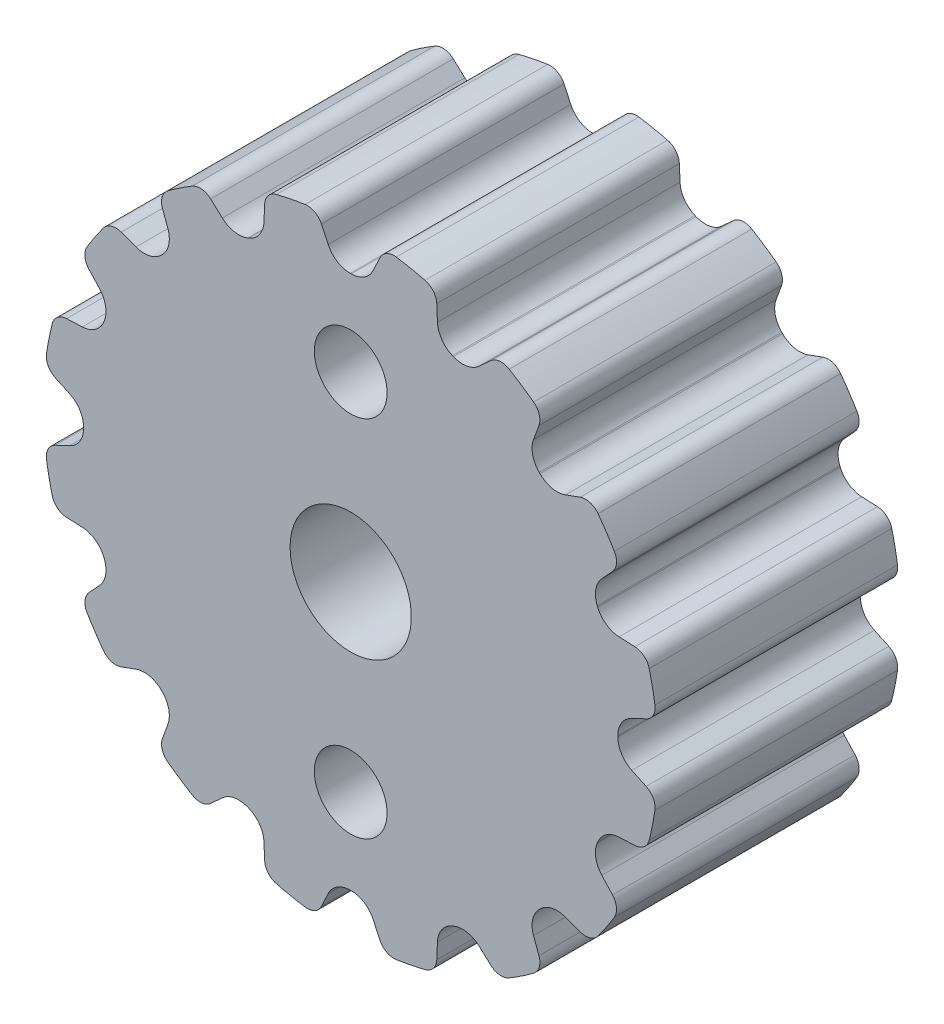
SolidWorks part; units mm, degrees
ref_plane "Спереди" through (0, 0, 0) normal (0, 0, 1) x (1, 0, 0)
ref_plane "Сверху" through (0, 0, 0) normal (0, 1, 0) x (1, 0, 0)
ref_plane "Справа" through (0, 0, 0) normal (1, 0, 0) x (0, 0, -1)
sketch "Эскиз1" plane through (0, 0, 0) normal (0, 0, 1) x (1, 0, 0)
  line L0 (-31.3394, -7.4998) -> (-31.3394, 5.1802) construction
  line L1 (-26.487, 4.215) -> (-31.3394, -7.4998) construction
  line L2 (-22.3733, 1.4663) -> (-31.3394, -7.4998) construction
  line L3 (-19.6246, -2.6474) -> (-31.3394, -7.4998) construction
  line L4 (-18.6594, -7.4998) -> (-31.3394, -7.4998) construction
  line L5 (-19.6246, -12.3523) -> (-31.3394, -7.4998) construction
  line L6 (-22.3733, -16.466) -> (-31.3394, -7.4998) construction
  line L7 (-26.487, -19.2146) -> (-31.3394, -7.4998) construction
  line L8 (-31.3394, -20.1798) -> (-31.3394, -7.4998) construction
  line L9 (-36.1919, -19.2146) -> (-31.3394, -7.4998) construction
  line L10 (-40.3056, -16.466) -> (-31.3394, -7.4998) construction
  line L11 (-43.0542, -12.3523) -> (-31.3394, -7.4998) construction
  line L12 (-44.0194, -7.4998) -> (-31.3394, -7.4998) construction
  line L13 (-43.0542, -2.6474) -> (-31.3394, -7.4998) construction
  line L14 (-40.3056, 1.4663) -> (-31.3394, -7.4998) construction
  line L15 (-36.1919, 4.215) -> (-31.3394, -7.4998) construction
  line L16 (-31.3624, 3.5104) -> (-31.3165, 3.5104)
  line L17 (-35.5741, 2.6635) -> (-35.5317, 2.6811)
  line L18 (-39.1411, 0.2694) -> (-39.1086, 0.3018)
  line L19 (-41.5203, -3.3076) -> (-41.5028, -3.2652)
  line L20 (-42.3497, -7.4769) -> (-42.3497, -7.5228)
  line L21 (-41.5203, -11.6921) -> (-41.5028, -11.7345)
  line L22 (-39.1411, -15.269) -> (-39.1086, -15.3015)
  line L23 (-35.5741, -17.6632) -> (-35.5317, -17.6807)
  line L24 (-31.3624, -18.5101) -> (-31.3165, -18.5101)
  line L25 (-27.1472, -17.6807) -> (-27.1048, -17.6632)
  line L26 (-23.5702, -15.3015) -> (-23.5378, -15.269)
  line L27 (-21.1585, -11.6921) -> (-21.1761, -11.7345)
  line L28 (-20.3292, -7.4769) -> (-20.3292, -7.5228)
  line L29 (-21.1761, -3.2652) -> (-21.1585, -3.3076)
  line L30 (-23.5702, 0.3018) -> (-23.5378, 0.2694)
  line L31 (-27.1472, 2.6811) -> (-27.1048, 2.6635)
  line L32 (-34.9153, 3.5613) -> (-34.8869, 4.2116)
  line L33 (-32.2687, 4.0878) -> (-32.5438, 4.6777)
  line L34 (-30.4102, 4.0878) -> (-30.1351, 4.6777)
  line L35 (-27.7636, 3.5613) -> (-27.7919, 4.2116)
  line L36 (-26.0465, 2.8501) -> (-25.5667, 3.2898)
  line L37 (-23.8028, 1.3509) -> (-23.5802, 1.9625)
  line L38 (-22.4887, 0.0368) -> (-21.8771, 0.2594)
  line L39 (-20.9895, -2.2069) -> (-20.5498, -1.7271)
  line L40 (-20.2783, -3.924) -> (-19.628, -3.9523)
  line L41 (-19.7518, -6.5706) -> (-19.1619, -6.2955)
  line L42 (-19.7518, -8.4291) -> (-19.1619, -8.7042)
  line L43 (-20.2783, -11.0757) -> (-19.628, -11.0473)
  line L44 (-20.9895, -12.7927) -> (-20.5498, -13.2726)
  line L45 (-22.4887, -15.0365) -> (-21.8771, -15.2591)
  line L46 (-23.8028, -16.3506) -> (-23.5802, -16.9622)
  line L47 (-26.0465, -17.8498) -> (-25.5667, -18.2895)
  line L48 (-27.7636, -18.561) -> (-27.7919, -19.2113)
  line L49 (-30.4102, -19.0875) -> (-30.1351, -19.6774)
  line L50 (-32.2687, -19.0875) -> (-32.5438, -19.6774)
  line L51 (-34.9153, -18.561) -> (-34.8869, -19.2113)
  line L52 (-36.6323, -17.8498) -> (-37.1122, -18.2895)
  line L53 (-38.8761, -16.3506) -> (-39.0987, -16.9622)
  line L54 (-40.1902, -15.0365) -> (-40.8018, -15.2591)
  line L55 (-41.6894, -12.7927) -> (-42.1291, -13.2726)
  line L56 (-42.4006, -11.0757) -> (-43.0509, -11.0473)
  line L57 (-42.9271, -8.4291) -> (-43.517, -8.7042)
  line L58 (-42.9271, -6.5706) -> (-43.517, -6.2955)
  line L59 (-42.4006, -3.924) -> (-43.0509, -3.9523)
  line L60 (-41.6894, -2.2069) -> (-42.1291, -1.7271)
  line L61 (-40.1902, 0.0368) -> (-40.8018, 0.2594)
  line L62 (-38.8761, 1.3509) -> (-39.0987, 1.9625)
  line L63 (-36.6323, 2.8501) -> (-37.1122, 3.2898)
  arc A0 (-28.2768, 4.8047) -> (-29.4602, 5.0401) centre (-31.3394, -7.4998) ccw
  arc A1 (-23.8011, 2.6961) -> (-24.8044, 3.3664) centre (-31.3394, -7.4998) ccw
  arc A2 (-20.4732, -0.9648) -> (-21.1435, 0.0385) centre (-31.3394, -7.4998) ccw
  arc A3 (-18.7995, -5.6206) -> (-19.0349, -4.4372) centre (-31.3394, -7.4998) ccw
  arc A4 (-19.0349, -10.5625) -> (-18.7995, -9.379) centre (-31.3394, -7.4998) ccw
  arc A5 (-21.1435, -15.0382) -> (-20.4732, -14.0348) centre (-31.3394, -7.4998) ccw
  arc A6 (-24.8044, -18.3661) -> (-23.8011, -17.6957) centre (-31.3394, -7.4998) ccw
  arc A7 (-29.4602, -20.0398) -> (-28.2768, -19.8044) centre (-31.3394, -7.4998) ccw
  arc A8 (-34.4021, -19.8044) -> (-33.2186, -20.0398) centre (-31.3394, -7.4998) ccw
  arc A9 (-38.8777, -17.6957) -> (-37.8744, -18.3661) centre (-31.3394, -7.4998) ccw
  arc A10 (-42.2057, -14.0348) -> (-41.5353, -15.0382) centre (-31.3394, -7.4998) ccw
  arc A11 (-43.8794, -9.379) -> (-43.644, -10.5625) centre (-31.3394, -7.4998) ccw
  arc A12 (-43.644, -4.4372) -> (-43.8794, -5.6206) centre (-31.3394, -7.4998) ccw
  arc A13 (-41.5353, 0.0385) -> (-42.2057, -0.9648) centre (-31.3394, -7.4998) ccw
  arc A14 (-37.8744, 3.3664) -> (-38.8777, 2.6961) centre (-31.3394, -7.4998) ccw
  arc A15 (-33.2187, 5.0401) -> (-34.4021, 4.8047) centre (-31.3394, -7.4998) ccw
  arc A16 (-37.1122, 3.2898) -> (-37.8744, 3.3664) centre (-37.5446, 2.818) ccw
  arc A17 (-34.8869, 4.2116) -> (-34.4021, 4.8047) centre (-34.2475, 4.1837) cw
  arc A18 (-32.5438, 4.6777) -> (-33.2187, 5.0401) centre (-33.1239, 4.4072) ccw
  arc A19 (-30.1351, 4.6777) -> (-29.4602, 5.0401) centre (-29.5551, 4.4072) cw
  arc A20 (-27.7919, 4.2116) -> (-28.2768, 4.8047) centre (-28.4313, 4.1837) ccw
  arc A21 (-25.5667, 3.2898) -> (-24.8044, 3.3664) centre (-25.1343, 2.818) cw
  arc A22 (-23.5802, 1.9625) -> (-23.8011, 2.6961) centre (-24.1816, 2.1814) ccw
  arc A23 (-21.8771, 0.2594) -> (-21.1435, 0.0385) centre (-21.6582, -0.342) cw
  arc A24 (-20.5498, -1.7271) -> (-20.4732, -0.9648) centre (-21.0216, -1.2947) ccw
  arc A25 (-19.1619, -6.2955) -> (-18.7995, -5.6206) centre (-19.4324, -5.7155) ccw
  arc A26 (-19.0349, -4.4372) -> (-19.628, -3.9523) centre (-19.6559, -4.5917) ccw
  arc A27 (-18.7995, -9.379) -> (-19.1619, -8.7042) centre (-19.4324, -9.2842) ccw
  arc A28 (-19.0349, -10.5625) -> (-19.628, -11.0473) centre (-19.6559, -10.4079) cw
  arc A29 (-20.5498, -13.2726) -> (-20.4732, -14.0348) centre (-21.0216, -13.705) cw
  arc A30 (-21.1435, -15.0382) -> (-21.8771, -15.2591) centre (-21.6582, -14.6577) cw
  arc A31 (-23.5802, -16.9622) -> (-23.8011, -17.6957) centre (-24.1816, -17.1811) cw
  arc A32 (-24.8044, -18.3661) -> (-25.5667, -18.2895) centre (-25.1343, -17.8177) cw
  arc A33 (-27.7919, -19.2113) -> (-28.2768, -19.8044) centre (-28.4313, -19.1834) cw
  arc A34 (-29.4602, -20.0398) -> (-30.1351, -19.6774) centre (-29.5551, -19.4069) cw
  arc A35 (-32.5438, -19.6774) -> (-33.2186, -20.0398) centre (-33.1238, -19.4069) cw
  arc A36 (-34.4021, -19.8044) -> (-34.8869, -19.2113) centre (-34.2475, -19.1834) cw
  arc A37 (-37.1122, -18.2895) -> (-37.8744, -18.3661) centre (-37.5446, -17.8177) cw
  arc A38 (-38.8777, -17.6957) -> (-39.0987, -16.9622) centre (-38.4973, -17.1811) cw
  arc A39 (-40.8018, -15.2591) -> (-41.5353, -15.0382) centre (-41.0207, -14.6577) cw
  arc A40 (-42.2057, -14.0348) -> (-42.1291, -13.2726) centre (-41.6573, -13.705) cw
  arc A41 (-43.0509, -11.0473) -> (-43.644, -10.5625) centre (-43.023, -10.4079) cw
  arc A42 (-43.8794, -9.379) -> (-43.517, -8.7042) centre (-43.2465, -9.2842) cw
  arc A43 (-43.517, -6.2955) -> (-43.8794, -5.6206) centre (-43.2465, -5.7155) cw
  arc A44 (-43.644, -4.4372) -> (-43.0509, -3.9523) centre (-43.023, -4.5917) cw
  arc A45 (-42.1291, -1.7271) -> (-42.2057, -0.9648) centre (-41.6573, -1.2947) cw
  arc A46 (-41.5353, 0.0385) -> (-40.8018, 0.2594) centre (-41.0207, -0.342) cw
  arc A47 (-39.0987, 1.9625) -> (-38.8777, 2.6961) centre (-38.4973, 2.1814) cw
  arc A48 (-30.4102, 4.0878) -> (-31.3165, 3.5104) centre (-31.3165, 4.5104) cw
  arc A49 (-31.3624, 3.5104) -> (-32.2687, 4.0878) centre (-31.3624, 4.5104) cw
  arc A50 (-26.0465, 2.8501) -> (-27.1048, 2.6635) centre (-26.7221, 3.5874) cw
  arc A51 (-27.1472, 2.6811) -> (-27.7636, 3.5613) centre (-26.7645, 3.6049) cw
  arc A52 (-23.8028, 1.3509) -> (-23.5702, 0.3018) centre (-22.8631, 1.0089) ccw
  arc A53 (-22.4887, 0.0368) -> (-23.5378, 0.2694) centre (-22.8307, 0.9765) cw
  arc A54 (-20.9895, -2.2069) -> (-21.1761, -3.2652) centre (-20.2522, -2.8825) ccw
  arc A55 (-20.2783, -3.924) -> (-21.1585, -3.3076) centre (-20.2347, -2.9249) cw
  arc A56 (-19.7518, -6.5706) -> (-20.3292, -7.4769) centre (-19.3292, -7.4769) ccw
  arc A57 (-20.3292, -7.5228) -> (-19.7518, -8.4291) centre (-19.3292, -7.5228) ccw
  arc A58 (-20.2783, -11.0757) -> (-21.1585, -11.6921) centre (-20.2347, -12.0748) ccw
  arc A59 (-21.1761, -11.7345) -> (-20.9895, -12.7927) centre (-20.2522, -12.1171) ccw
  arc A60 (-22.4887, -15.0365) -> (-23.5378, -15.269) centre (-22.8307, -15.9761) ccw
  arc A61 (-23.5702, -15.3015) -> (-23.8028, -16.3506) centre (-22.8631, -16.0086) ccw
  arc A62 (-26.0465, -17.8498) -> (-27.1048, -17.6632) centre (-26.7221, -18.5871) ccw
  arc A63 (-27.1472, -17.6807) -> (-27.7636, -18.561) centre (-26.7645, -18.6046) ccw
  arc A64 (-30.4102, -19.0875) -> (-31.3165, -18.5101) centre (-31.3165, -19.5101) ccw
  arc A65 (-31.3624, -18.5101) -> (-32.2687, -19.0875) centre (-31.3624, -19.5101) ccw
  arc A66 (-34.9153, -18.561) -> (-35.5317, -17.6807) centre (-35.9144, -18.6046) ccw
  arc A67 (-35.5741, -17.6632) -> (-36.6323, -17.8498) centre (-35.9567, -18.5871) ccw
  arc A68 (-38.8761, -16.3506) -> (-39.1086, -15.3015) centre (-39.8157, -16.0086) ccw
  arc A69 (-39.1411, -15.269) -> (-40.1902, -15.0365) centre (-39.8482, -15.9761) ccw
  arc A70 (-41.6894, -12.7927) -> (-41.5028, -11.7345) centre (-42.4267, -12.1171) ccw
  arc A71 (-41.5203, -11.6921) -> (-42.4006, -11.0757) centre (-42.4442, -12.0748) ccw
  arc A72 (-42.9271, -8.4291) -> (-42.3497, -7.5228) centre (-43.3497, -7.5228) ccw
  arc A73 (-42.3497, -7.4769) -> (-42.9271, -6.5706) centre (-43.3497, -7.4769) ccw
  arc A74 (-42.4006, -3.924) -> (-41.5203, -3.3076) centre (-42.4442, -2.9249) ccw
  arc A75 (-41.5028, -3.2652) -> (-41.6894, -2.2069) centre (-42.4267, -2.8825) ccw
  arc A76 (-39.1411, 0.2694) -> (-40.1902, 0.0368) centre (-39.8482, 0.9765) cw
  arc A77 (-39.1086, 0.3018) -> (-38.8761, 1.3509) centre (-39.8157, 1.0089) ccw
  arc A78 (-36.6323, 2.8501) -> (-35.5741, 2.6635) centre (-35.9567, 3.5874) ccw
  arc A79 (-35.5317, 2.6811) -> (-34.9153, 3.5613) centre (-35.9144, 3.6049) ccw
  point P147 (-30.6794, 3.5104)
  point P150 (-31.9995, 3.5104)
  point P153 (-26.5162, 2.4197)
  point P156 (-27.7358, 2.9249)
  point P159 (-24.0207, 0.7523)
  point P162 (-23.0873, -0.1811)
  point P165 (-21.4199, -2.6766)
  point P168 (-20.9147, -3.8962)
  point P171 (-20.3292, -6.8398)
  point P174 (-20.3292, -8.1598)
  point P177 (-20.9147, -11.1035)
  point P180 (-21.4199, -12.323)
  point P183 (-23.0873, -14.8186)
  point P186 (-24.0207, -15.7519)
  point P189 (-26.5162, -17.4194)
  point P192 (-27.7358, -17.9245)
  point P195 (-30.6794, -18.5101)
  point P198 (-31.9994, -18.5101)
  point P201 (-34.9431, -17.9245)
  point P204 (-36.1626, -17.4194)
  point P207 (-38.6582, -15.7519)
  point P210 (-39.5915, -14.8186)
  point P213 (-41.259, -12.323)
  point P216 (-41.7641, -11.1035)
  point P219 (-42.3497, -8.1598)
  point P222 (-42.3497, -6.8398)
  point P225 (-41.7641, -3.8962)
  point P228 (-41.259, -2.6766)
  point P231 (-39.5915, -0.1811)
  point P234 (-38.6582, 0.7523)
  point P237 (-36.1626, 2.4197)
  point P240 (-34.9431, 2.9249)
  dimension "D1" = 0.66
  dimension "D3" = 0.66
  dimension "D65" = 0.64
  dimension "D66" = 1
  dimension "D67" = 0.023
  dimension "D4" = 1.32
  dimension "D5" = 0.66
  dimension "D6" = 1.32
  dimension "D7" = 0.66
  dimension "D8" = 1.32
  dimension "D9" = 1.32
  dimension "D10" = 0.66
  dimension "D11" = 0.66
  dimension "D12" = 1.32
  dimension "D13" = 1.32
  dimension "D14" = 0.66
  dimension "D15" = 1.32
  dimension "D16" = 0.66
  dimension "D17" = 1.32
  dimension "D18" = 0.66
  dimension "D19" = 1.32
  dimension "D20" = 0.66
  dimension "D21" = 1.32
  dimension "D22" = 0.66
  dimension "D23" = 1.32
  dimension "D24" = 0.66
  dimension "D25" = 1.32
  dimension "D26" = 0.66
  dimension "D27" = 1.32
  dimension "D28" = 0.66
  dimension "D29" = 1.32
  dimension "D30" = 0.66
  dimension "D31" = 1.32
  dimension "D32" = 0.66
  dimension "D33" = 25
  dimension "D34" = 25
  dimension "D35" = 25
  dimension "D36" = 25
  dimension "D37" = 25
  dimension "D38" = 25
  dimension "D39" = 25
  dimension "D40" = 25
  dimension "D41" = 25
  dimension "D42" = 25
  dimension "D43" = 25
  dimension "D44" = 25
  dimension "D45" = 25
  dimension "D46" = 25
  dimension "D47" = 25
  dimension "D48" = 25
  dimension "D49" = 25
  dimension "D50" = 25
  dimension "D51" = 25
  dimension "D52" = 25
  dimension "D53" = 25
  dimension "D54" = 25
  dimension "D55" = 25
  dimension "D56" = 25
  dimension "D57" = 25
  dimension "D58" = 25
  dimension "D59" = 25
  dimension "D60" = 25
  dimension "D61" = 25
  dimension "D62" = 25
  dimension "D63" = 25
  dimension "D64" = 25
extrude "Бобышка-Вытянуть2" add sketch "Эскиз1" along normal blind 10
sketch "Эскиз2" plane through (0, 0, 0) normal (0, 0, -1) x (-1, 0, 0)
  line L0 (31.3394, 0.0002) -> (31.3394, -14.9998) construction
  line L1 (31.3394, -14.9998) -> (38.8394, -7.4998) construction
  line L2 (38.8394, -7.4998) -> (23.8394, -7.4998) construction
  circle A0 centre (31.3394, -7.4998) radius 7.5 construction
  circle A1 centre (31.3394, 0.0002) radius 1.5
  circle A2 centre (31.3394, -14.9998) radius 1.5
  circle A3 centre (31.3394, -7.4998) radius 2.5
  dimension "D1" = 15
  dimension "D2" = 3
  dimension "D3" = 3
  dimension "D4" = 5
extrude "Вырез-Вытянуть1" cut sketch "Эскиз2" against normal blind 10
